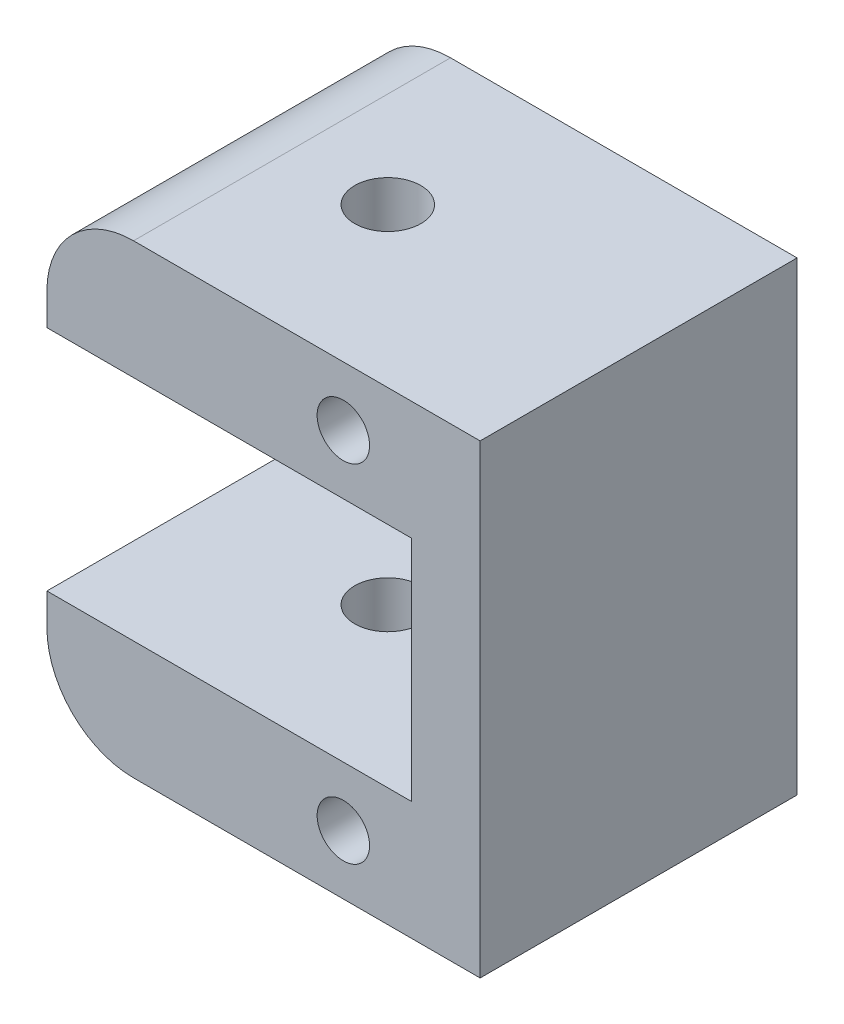
SolidWorks part; units mm, degrees
ref_plane "Face" through (0, 0, 0) normal (0, 0, 1) x (1, 0, 0)
ref_plane "Dessus" through (0, 0, 0) normal (0, 1, 0) x (1, 0, 0)
ref_plane "Droite" through (0, 0, 0) normal (1, 0, 0) x (0, 0, -1)
sketch "Sketch1" plane through (0, 0, 0) normal (0, 0, 1) x (1, 0, 0)
  line L0 (-8, 10.2) -> (-8, 5)
  line L1 (-8, 5) -> (8, 5)
  line L2 (8, 5) -> (8, -5)
  line L3 (8, -5) -> (-8, -5)
  line L4 (-8, -5) -> (-8, -10.2)
  line L5 (-8, -10.2) -> (11, -10.2)
  line L6 (11, -10.2) -> (11, 10.2)
  line L7 (11, 10.2) -> (-8, 10.2)
  dimension "D1" = 5.2
  dimension "D2" = 5.2
  dimension "D3" = 16
  dimension "D4" = 16
  dimension "D5" = 10
  dimension "D6" = 3
  dimension "D7" = 5
  dimension "D8" = 8
extrude "Boss-Extrude2" add sketch "Sketch1" against normal blind 13.9
sketch "Sketch2" plane through (0, 0, 0) normal (0, 0, 1) x (1, 0, 0)
  circle A0 centre (5, 7.6) radius 1.15
  circle A1 centre (5, -7.6) radius 1.15
  dimension "D3" = 2.3
  dimension "D1" = 2.6
  dimension "D2" = 3
  dimension "D4" = 2
extrude "Cut-Extrude1" cut sketch "Sketch2" against normal through all and the other way through all
sketch "Sketch3" plane through (0, 10.2, 0) normal (0, 1, 0) x (1, 0, 0)
  circle A0 centre (0, 6.95) radius 1.45
  dimension "D1" = 2.9
  dimension "D2" = 8
  dimension "D3" = 6.95
extrude "Cut-Extrude2" cut sketch "Sketch3" against normal through all
fillet "Fillet1" radius 3.8 2 edges at (-8, -10.2, -6.95) (-8, 10.2, -6.95)
